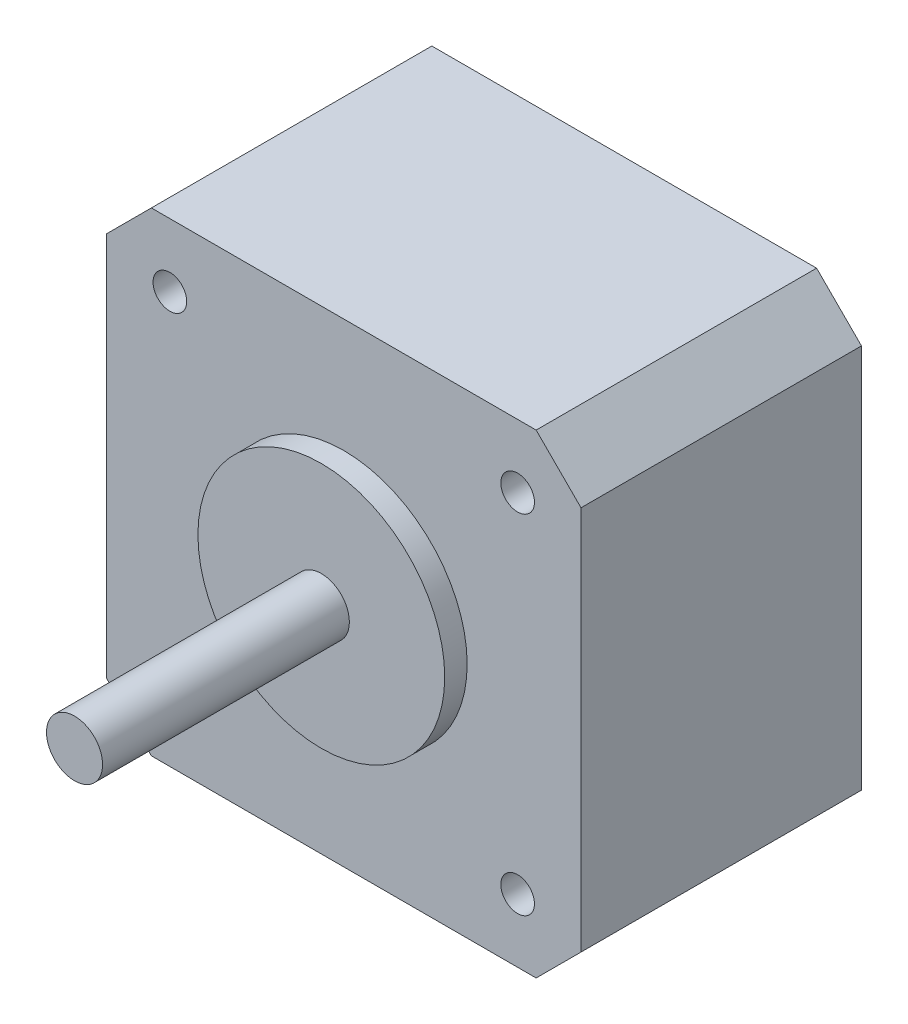
SolidWorks part; units mm, degrees
ref_plane "Front Plane" through (0, 0, 0) normal (0, 0, 1) x (1, 0, 0)
ref_plane "Top Plane" through (0, 0, 0) normal (0, 1, 0) x (1, 0, 0)
ref_plane "Right Plane" through (0, 0, 0) normal (1, 0, 0) x (0, 0, -1)
sketch "Sketch1" plane through (0, 0, 0) normal (0, 0, 1) x (1, 0, 0)
  line L1 (-21.15, 21.15) -> (21.15, 21.15)
  line L2 (-21.15, 21.15) -> (-21.15, -21.15)
  line L3 (-21.15, -21.15) -> (21.15, -21.15)
  line L4 (21.15, 21.15) -> (21.15, -21.15)
  line L5 (-21.15, 21.15) -> (21.15, -21.15) construction
  line L6 (-21.15, -21.15) -> (21.15, 21.15) construction
  point P0 (0, 0)
  dimension "D1" = 42.3
extrude "Boss-Extrude1" add sketch "Sketch1" against normal blind 25
sketch "Sketch2" plane through (0, 0, 0) normal (0, 0, 1) x (1, 0, 0)
  line L1 (-15.5, 15.5) -> (15.5, 15.5) construction
  line L2 (-15.5, 15.5) -> (-15.5, -15.5) construction
  line L3 (-15.5, -15.5) -> (15.5, -15.5) construction
  line L4 (15.5, 15.5) -> (15.5, -15.5) construction
  line L5 (-15.5, 15.5) -> (15.5, -15.5) construction
  line L6 (-15.5, -15.5) -> (15.5, 15.5) construction
  circle A0 centre (-15.5, 15.5) radius 1.5
  circle A1 centre (15.5, 15.5) radius 1.5
  circle A2 centre (15.5, -15.5) radius 1.5
  circle A3 centre (-15.5, -15.5) radius 1.5
  point P0 (0, 0)
  dimension "D2" = 3
  dimension "D1" = 31
extrude "Cut-Extrude1" cut sketch "Sketch2" against normal blind 6
sketch "Sketch3" plane through (0, 0, 0) normal (0, 0, 1) x (1, 0, 0)
  circle A0 centre (0, 0) radius 11
  dimension "D1" = 22
extrude "Boss-Extrude2" add sketch "Sketch3" along normal blind 2
sketch "Sketch4" plane through (0, 0, 2) normal (0, 0, 1) x (1, 0, 0)
  circle A0 centre (0, 0) radius 2.5
  dimension "D1" = 5
extrude "Boss-Extrude3" add sketch "Sketch4" along normal offset from surface (22 mm away) 24 up to face at (11, 0, 0) offset beyond the face yes
chamfer "Chamfer1" distance 4 angle 45 4 edges at (-21.15, -21.15, -12.5) (21.15, -21.15, -12.5) (21.15, 21.15, -12.5) (-21.15, 21.15, -12.5)
